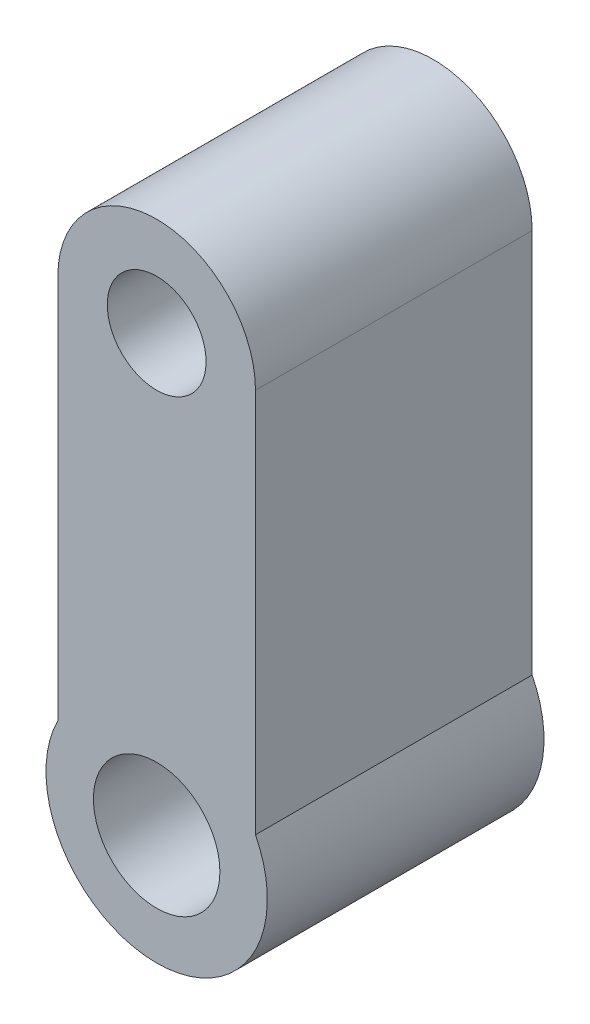
SolidWorks part; units mm, degrees
ref_plane "Front Plane" through (0, 0, 0) normal (0, 0, 1) x (1, 0, 0)
ref_plane "Top Plane" through (0, 0, 0) normal (0, 1, 0) x (1, 0, 0)
ref_plane "Right Plane" through (0, 0, 0) normal (1, 0, 0) x (0, 0, -1)
sketch "Sketch1" plane through (0, 0, 0) normal (0, 0, 1) x (1, 0, 0)
  line L0 (25, 12.6095) -> (25, 110.2284)
  line L1 (-25, 12.6095) -> (-25, 110.2284)
  line L2 (0, 110) -> (-12.5, 110) construction
  line L3 (-77.5, 110) -> (-85, 110) construction
  line L6 (-85, 92) -> (-25, 92)
  line L7 (-84.7599, 128) -> (-17.3494, 128)
  line L10 (-25, 110.2284) -> (-24.999, 110.2284) construction
  circle A0 centre (0, 0) radius 28
  circle A1 centre (0, 110) radius 25
  circle A2 centre (0, 0) radius 16
  circle A3 centre (0, 110) radius 12.5
  circle A4 centre (-85, 110) radius 7.5
  circle A5 centre (-85, 110) radius 18
  point P13 (0, 0)
  point P15 (-51.0546, 128)
  point P16 (0, 0)
  dimension "D2" = 56
  dimension "D3" = 32
  dimension "D4" = 50
  dimension "D5" = 25
  dimension "D9" = 15
  dimension "36" = 36
  dimension "D1" = 110
  dimension "D6" = 36
  dimension "D8" = 85
  dimension "D7" = 18
extrude "Boss-Extrude1" add sketch "Sketch1" along normal mid plane 70 contours A1 L1 A0 L0 | A1 A3 | A0 A2
